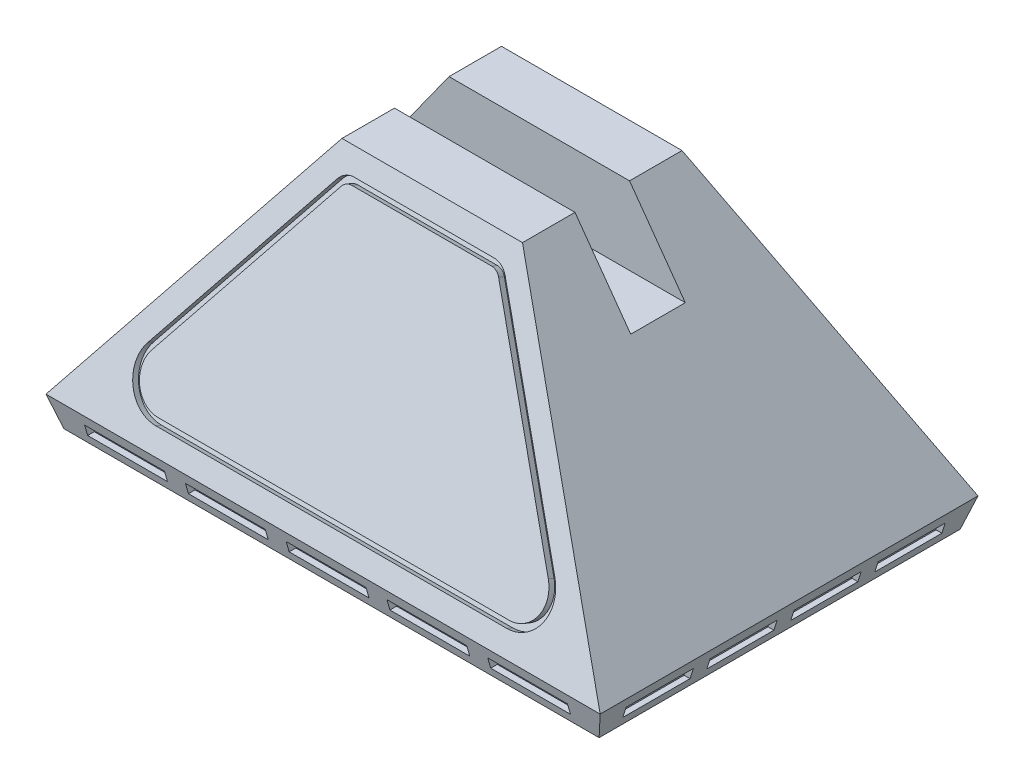
SolidWorks part; units mm, degrees
material "3.3320 (EN-AW 5019)"
ref_plane "Спереди" through (0, 0, 0) normal (0, 0, 1) x (1, 0, 0)
ref_plane "Сверху" through (0, 0, 0) normal (0, 1, 0) x (1, 0, 0)
ref_plane "Справа" through (0, 0, 0) normal (1, 0, 0) x (0, 0, -1)
sketch "Эскиз1" plane through (0, 0, 0) normal (0, 1, 0) x (1, 0, 0)
  line L1 (-123.5, -81.5) -> (123.5, -81.5)
  line L2 (-123.5, -81.5) -> (-123.5, 81.5)
  line L3 (-123.5, 81.5) -> (123.5, 81.5)
  line L4 (123.5, -81.5) -> (123.5, 81.5)
  line L5 (-123.5, -81.5) -> (123.5, 81.5) construction
  line L6 (-123.5, 81.5) -> (123.5, -81.5) construction
  point P0 (0, 0)
  dimension "D1" = 247
  dimension "D2" = 163
ref_plane "Плоскость1" through (0, 3, 0) normal (0, 1, 0) x (1, 0, 0)
sketch "Эскиз2" plane through (0, 3, 0) normal (0, 1, 0) x (1, 0, 0)
  line L1 (-124.5, -82.5) -> (124.5, -82.5)
  line L2 (-124.5, -82.5) -> (-124.5, 82.5)
  line L3 (-124.5, 82.5) -> (124.5, 82.5)
  line L4 (124.5, -82.5) -> (124.5, 82.5)
  line L5 (-124.5, -82.5) -> (124.5, 82.5) construction
  line L6 (-124.5, 82.5) -> (124.5, -82.5) construction
  point P0 (0, 0)
  dimension "D1" = 249
  dimension "D2" = 165
loft "По сечениям1" add profiles "Эскиз1", "Эскиз2"
ref_plane "Плоскость2" through (0, 17, 0) normal (0, 1, 0) x (1, 0, 0)
sketch "Эскиз3" plane through (0, 3, 0) normal (0, 1, 0) x (1, 0, 0)
  line L1 (-127.5, -86) -> (127.5, -86)
  line L2 (-127.5, -86) -> (-127.5, 86)
  line L3 (-127.5, 86) -> (127.5, 86)
  line L4 (127.5, -86) -> (127.5, 86)
  line L5 (-127.5, -86) -> (127.5, 86) construction
  line L6 (-127.5, 86) -> (127.5, -86) construction
  point P0 (0, 0)
  dimension "D1" = 255
  dimension "D2" = 172
sketch "Эскиз4" plane through (0, 17, 0) normal (0, 1, 0) x (1, 0, 0)
  line L1 (-132, -90) -> (132, -90)
  line L2 (-132, -90) -> (-132, 90)
  line L3 (-132, 90) -> (132, 90)
  line L4 (132, -90) -> (132, 90)
  line L5 (-132, -90) -> (132, 90) construction
  line L6 (-132, 90) -> (132, -90) construction
  point P0 (0, 0)
  dimension "D1" = 264
  dimension "D2" = 180
loft "По сечениям2" add profiles "Эскиз3", "Эскиз4"
ref_plane "Плоскость3" through (0, 141, 0) normal (0, 1, 0) x (1, 0, 0)
sketch "Эскиз5" plane through (0, 141, 0) normal (0, 1, 0) x (1, 0, 0)
  line L1 (-43, -38) -> (43, -38)
  line L2 (-43, -38) -> (-43, 38)
  line L3 (-43, 38) -> (43, 38)
  line L4 (43, -38) -> (43, 38)
  line L5 (-43, -38) -> (43, 38) construction
  line L6 (-43, 38) -> (43, -38) construction
  point P0 (0, 0)
  dimension "D1" = 86
  dimension "D2" = 76
loft "По сечениям3" add profiles "Эскиз5" section face at (0, 17, 0) section "Эскиз5"
sketch "Эскиз6" plane through (0, 0, 0) normal (1, 0, 0) x (0, 0, -1)
  line L0 (38, 141) -> (-38, 141) construction
  line L1 (38, 141) -> (-38, 141) construction
  line L2 (13, 141) -> (13, 104)
  line L3 (13, 104) -> (-13, 104)
  line L4 (-13, 104) -> (-13, 141)
  line L5 (-13, 141) -> (13, 141)
  point P4 (0, 141)
  dimension "D1" = 26
  dimension "D2" = 37
extrude "Вырез-Вытянуть1" cut sketch "Эскиз6" against normal through all and the other way through all
ref_plane "Плоскость4" through (132, 0, 0) normal (1, 0, 0) x (0, 0, -1)
sketch "Эскиз7" plane through (132, 0, 0) normal (1, 0, 0) x (0, 0, -1)
  line L0 (0, -4.4841) -> (0, 24.7282) construction
  line L1 (-36, 12) -> (-4, 12)
  line L2 (-36, 12) -> (-36, 7)
  line L3 (-36, 7) -> (-4, 7)
  line L4 (-4, 12) -> (-4, 7)
  line L5 (-76, 12) -> (-44, 12)
  line L6 (-76, 12) -> (-76, 7)
  line L7 (-76, 7) -> (-44, 7)
  line L8 (-44, 12) -> (-44, 7)
  line L9 (-86, 3) -> (86, 3) construction
  line L10 (76, 12) -> (76, 7)
  line L11 (76, 7) -> (44, 7)
  line L12 (44, 12) -> (44, 7)
  line L13 (76, 12) -> (44, 12)
  line L14 (36, 12) -> (36, 7)
  line L15 (36, 7) -> (4, 7)
  line L16 (4, 12) -> (4, 7)
  line L17 (36, 12) -> (4, 12)
  dimension "D1" = 8
  dimension "D2" = 4
  dimension "D3" = 32
  dimension "D4" = 5
  dimension "D5" = 4
extrude "Вырез-Вытянуть2" cut sketch "Эскиз7" along direction (1, 0, 0) on the side against the normal blind 6
mirror "Зеркальное отражение1" about plane through (0, 0, 0) normal (1, 0, 0) of "Вырез-Вытянуть2"
ref_plane "Плоскость5" through (0, 0, 90) normal (0, 0, 1) x (1, 0, 0)
sketch "Эскиз8" plane through (0, 0, 90) normal (0, 0, 1) x (1, 0, 0)
  line L0 (0, -4.7293) -> (0, 25.8192) construction
  line L1 (-127.5, 3) -> (127.5, 3) construction
  line L2 (-115, 12) -> (-77, 12)
  line L3 (-115, 12) -> (-115, 7)
  line L4 (-115, 7) -> (-77, 7)
  line L5 (-77, 12) -> (-77, 7)
  line L6 (-67, 12) -> (-29, 12)
  line L7 (-67, 12) -> (-67, 7)
  line L8 (-67, 7) -> (-29, 7)
  line L9 (-29, 12) -> (-29, 7)
  line L10 (-19, 12) -> (19, 12)
  line L11 (-19, 12) -> (-19, 7)
  line L12 (-19, 7) -> (19, 7)
  line L13 (19, 12) -> (19, 7)
  line L14 (29, 12) -> (67, 12)
  line L15 (29, 12) -> (29, 7)
  line L16 (29, 7) -> (67, 7)
  line L17 (67, 12) -> (67, 7)
  line L18 (77, 12) -> (115, 12)
  line L19 (77, 12) -> (77, 7)
  line L20 (77, 7) -> (115, 7)
  line L21 (115, 12) -> (115, 7)
  point P10 (0, 12)
  dimension "D1" = 38
  dimension "D2" = 5
  dimension "D3" = 4
  dimension "D5" = 10
  dimension "D4" = 5
extrude "Вырез-Вытянуть3" cut sketch "Эскиз8" against normal blind 6
mirror "Зеркальное отражение2" about plane through (0, 0, 0) normal (0, 0, 1) of "Вырез-Вытянуть3"
sketch "Эскиз9" plane through (0, 34.6398, 82.6027) normal (0, 0.3867, 0.9222) x (1, 0, 0)
  line L4 (-37.4978, 100.0935) -> (-94.4516, 14.0472)
  line L5 (-83.6112, -6.1281) -> (83.6112, -6.1281)
  line L6 (94.4516, 14.0472) -> (37.4978, 100.0935)
  line L7 (33.3283, 102.3338) -> (-33.3283, 102.3338)
  line L8 (113.3889, -9.1281) -> (37.6269, 105.3338)
  line L9 (37.6269, 105.3338) -> (-37.6269, 105.3338)
  line L10 (-37.6269, 105.3338) -> (-113.3889, -9.1281)
  line L11 (-113.3889, -9.1281) -> (113.3889, -9.1281)
  line L12 (96.9533, 15.703) -> (39.9994, 101.7493)
  line L13 (33.3283, 105.3338) -> (-33.3283, 105.3338)
  line L14 (-39.9994, 101.7493) -> (-96.9533, 15.703)
  line L15 (-83.6112, -9.1281) -> (83.6112, -9.1281)
  arc A0 (-96.9533, 15.703) -> (-83.6112, -9.1281) centre (-83.6112, 6.8719) ccw
  arc A1 (96.9533, 15.703) -> (83.6112, -9.1281) centre (83.6112, 6.8719) cw
  arc A2 (39.9994, 101.7493) -> (33.3283, 105.3338) centre (33.3283, 97.3338) ccw
  arc A3 (-33.3283, 105.3338) -> (-39.9994, 101.7493) centre (-33.3283, 97.3338) ccw
  arc A4 (-94.4516, 14.0472) -> (-83.6112, -6.1281) centre (-83.6112, 6.8719) ccw
  arc A5 (94.4516, 14.0472) -> (83.6112, -6.1281) centre (83.6112, 6.8719) cw
  arc A6 (37.4978, 100.0935) -> (33.3283, 102.3338) centre (33.3283, 97.3338) ccw
  arc A7 (-33.3283, 102.3338) -> (-37.4978, 100.0935) centre (-33.3283, 97.3338) ccw
  dimension "D2" = 16
  dimension "D3" = 8
  dimension "D1" = 10
  dimension "D4" = 3
extrude "Вырез-Вытянуть4" cut sketch "Эскиз9" against normal blind 3
mirror "Зеркальное отражение3" about plane through (0, 0, 0) normal (0, 0, 1) of "Вырез-Вытянуть4"
